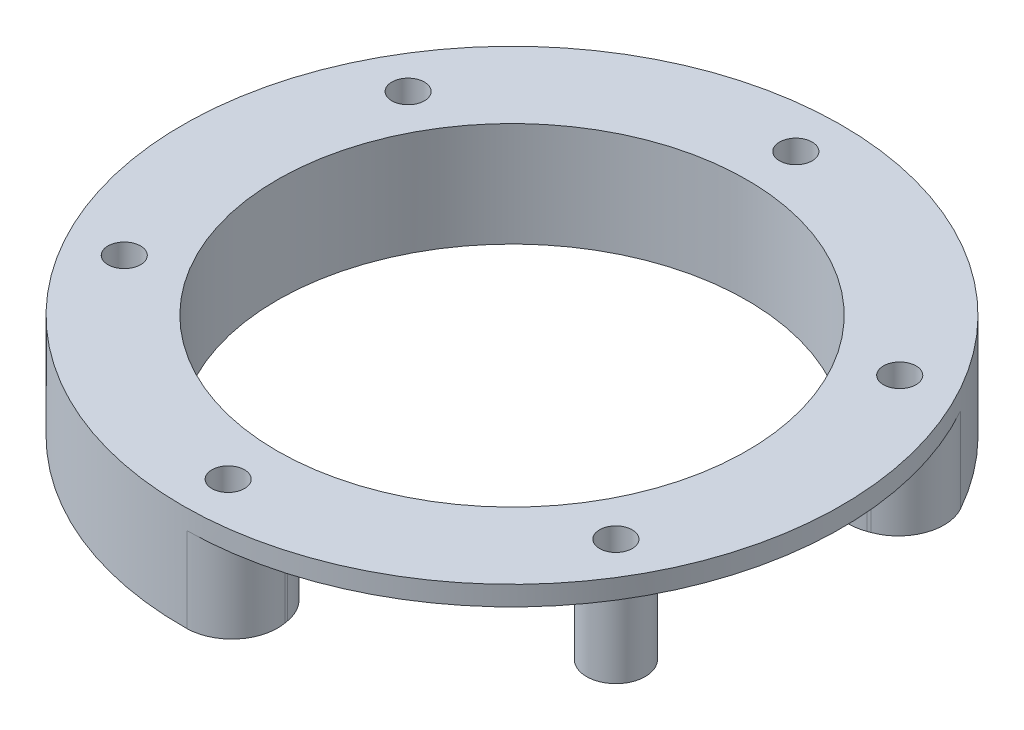
SolidWorks part; units mm, degrees
material "ABS"
ref_plane "Front Plane" through (0, 0, 0) normal (0, 0, 1) x (1, 0, 0)
ref_plane "Top Plane" through (0, 0, 0) normal (0, 1, 0) x (1, 0, 0)
ref_plane "Right Plane" through (0, 0, 0) normal (1, 0, 0) x (0, 0, -1)
sketch "Sketch1" plane through (0, 0, 0) normal (0, 1, 0) x (1, 0, 0)
  circle A0 centre (0, 0) radius 36
  circle A1 centre (0, 0) radius 50.5
  dimension "D2" = 72
  dimension "D1" = 14.5
extrude "Boss-Extrude1" add sketch "Sketch1" along normal blind 16
sketch "Sketch2" plane through (0, 16, 0) normal (0, 1, 0) x (1, 0, 0)
  circle A0 centre (0, 43.5) radius 2.5
  circle A2 centre (37.6721, 21.75) radius 2.5
  circle A3 centre (37.6721, -21.75) radius 2.5
  circle A4 centre (0, -43.5) radius 2.5
  circle A5 centre (-37.6721, -21.75) radius 2.5
  circle A6 centre (-37.6721, 21.75) radius 2.5
  circle A7 centre (0, 0) radius 43.5 construction
  dimension "D1" = 5
  dimension "D3" = 87
  dimension "D2" = 6
extrude "Cut-Extrude1" cut sketch "Sketch2" against normal through all
sketch "Sketch3" plane through (0, 0, 0) normal (0, -1, 0) x (1, 0, 0)
  line L0 (0, 0) -> (0, 50.5) construction
  line L1 (0, 0) -> (8.7692, 49.7328)
  line L2 (0, 0) -> (47.4545, -17.272)
  circle A0 centre (0, 0) radius 50.5 construction
  arc A2 (47.4545, -17.272) -> (8.7692, 49.7328) centre (0, 0) ccw
  circle A5 centre (37.6721, 21.75) radius 4.5
  circle A6 centre (37.6721, 21.75) radius 4.5
  dimension "D2" = 100
  dimension "D1" = 10
  dimension "D3" = 2
extrude "Cut-Extrude2" cut sketch "Sketch3" against normal offset from surface (13 mm away) 3 up to face at (0, 16, -41)
fillet "Fillet1" radius 7 4 edges at (6.2513, 6.5, 35.4531) (8.7692, 6.5, 49.7328) (33.8289, 6.5, -12.3127) (47.4545, 6.5, -17.272)
